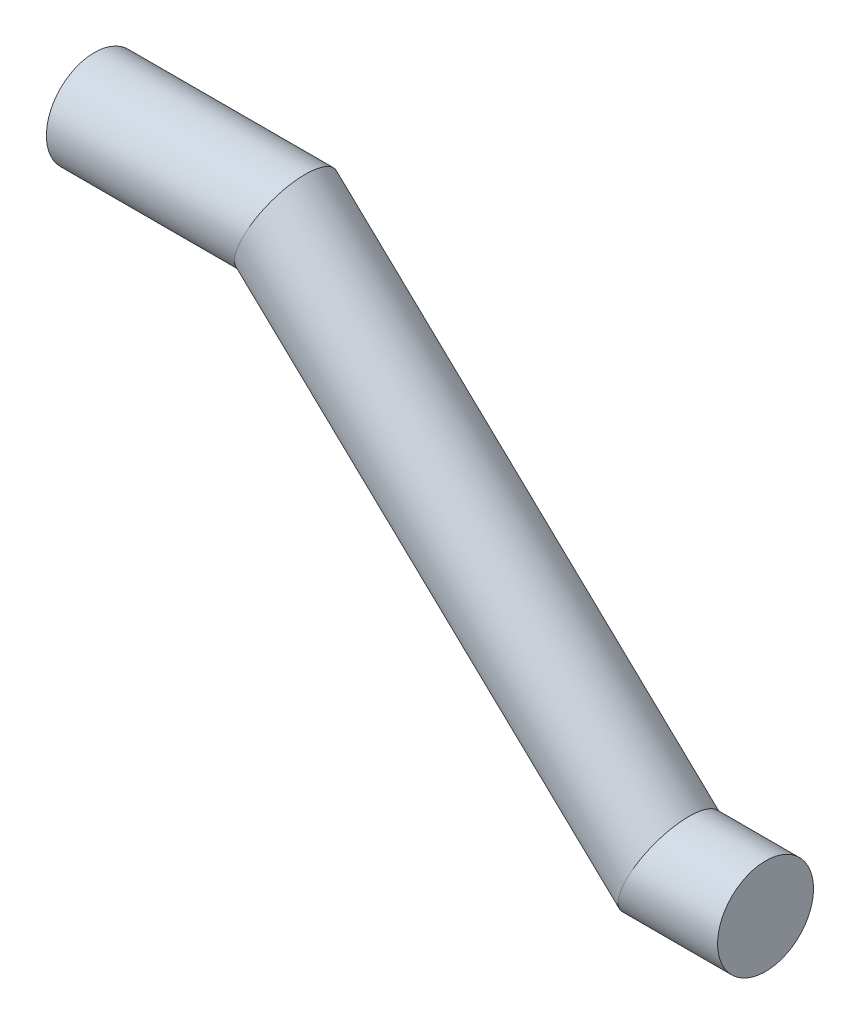
SolidWorks part; units mm, degrees
ref_plane "Front Plane" through (0, 0, 0) normal (0, 0, 1) x (1, 0, 0)
ref_plane "Top Plane" through (0, 0, 0) normal (0, 1, 0) x (1, 0, 0)
ref_plane "Right Plane" through (0, 0, 0) normal (1, 0, 0) x (0, 0, -1)
sketch "Sketch1" plane through (0, 0, 0) normal (1, 0, 0) x (0, 0, -1)
  circle A0 centre (0, 0) radius 25
  dimension "D1" = 50
sketch "Sketch2" plane through (0, 0, 0) normal (0, 0, 1) x (1, 0, 0)
  line L0 (0, 0) -> (100, 0)
  line L1 (0, -25) -> (0, 25) construction
  line L2 (100, 0) -> (300, -190)
  line L3 (300, -190) -> (350, -190)
  line L4 (100, 0) -> (100, -522.7742) construction
  line L5 (300, -190) -> (100, -190) construction
  point P8 (0, 0)
  dimension "D1" = 100
  dimension "D2" = 190
  dimension "D3" = 50
  dimension "D4" = 200
sweep "Sweep1" add profiles "Sketch1" path "Sketch2"
